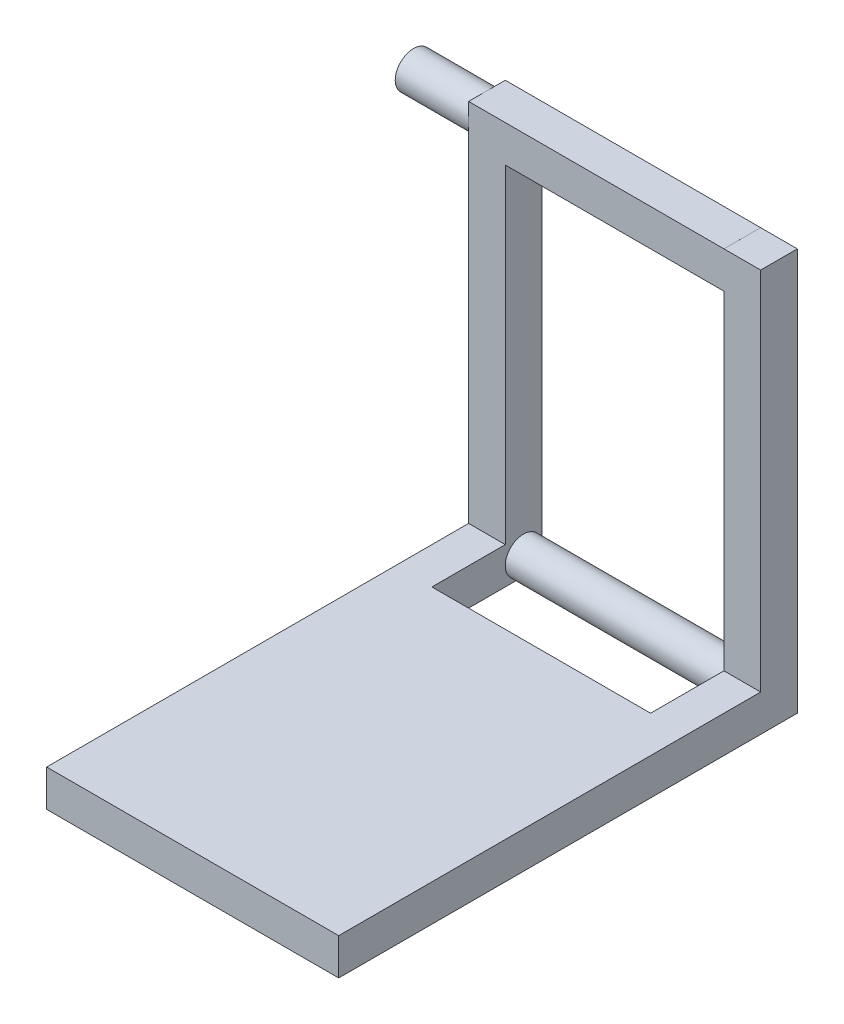
SolidWorks part; units mm, degrees
ref_plane "Front Plane" through (0, 0, 0) normal (0, 0, 1) x (1, 0, 0)
ref_plane "Top Plane" through (0, 0, 0) normal (0, 1, 0) x (1, 0, 0)
ref_plane "Right Plane" through (0, 0, 0) normal (1, 0, 0) x (0, 0, -1)
sketch "Sketch2" plane through (0, 0, 0) normal (0, 1, 0) x (1, 0, 0)
  line L1 (-0.4885, 0.9749) -> (1.5115, 0.9749)
  line L2 (-0.4885, 0.9749) -> (-0.4885, -1.0251)
  line L3 (-0.4885, -1.0251) -> (1.5115, -1.0251)
  line L4 (1.5115, 0.9749) -> (1.5115, -1.0251)
  dimension "D1" = 2
extrude "Boss-Extrude2" add sketch "Sketch2" along normal blind 21.92
ref_plane "Plane1" through (1.5115, 0, 0) normal (1, 0, 0) x (0, 0, -1)
sketch "Sketch3" plane through (1.5115, 0, 0) normal (1, 0, 0) x (0, 0, -1)
  circle A0 centre (-0.0297, 0.9996) radius 1
  dimension "D1" = 2
extrude "Boss-Extrude3" add sketch "Sketch3" along normal blind 11.92 contours A0
ref_plane "Plane3" through (-0.4885, 0, 0) normal (-1, 0, 0) x (0, 0, 1)
sketch "Sketch5" plane through (-0.4885, 0, 0) normal (-1, 0, 0) x (0, 0, 1)
  line L0 (1.0251, 21.92) -> (1.0251, 0) construction
  line L1 (-0.9749, 21.92) -> (1.0251, 21.92) construction
  circle A0 centre (0.0251, 20.92) radius 1
  dimension "D1" = 2
extrude "Boss-Extrude5" add sketch "Sketch5" along normal blind 4
ref_plane "Plane4" through (13.4315, 0, 0) normal (1, 0, 0) x (0, 0, -1)
sketch "Sketch6" plane through (13.4315, 0, 0) normal (1, 0, 0) x (0, 0, -1)
  line L1 (-0.7368, 1.7067) -> (0.6774, 1.7067)
  line L2 (-0.7368, 1.7067) -> (-0.7368, 0.2925)
  line L3 (-0.7368, 0.2925) -> (0.6774, 0.2925)
  line L4 (0.6774, 1.7067) -> (0.6774, 0.2925)
  circle A0 centre (-0.0297, 0.9996) radius 1 construction
  arc A1 (0, 0) -> (-1.0251, 1.0958) centre (-0.0297, 0.9996) ccw construction
  point P4 (0, 0)
  point P7 (0, 0)
  point P8 (0, 0)
  point P9 (0, 0)
sketch "Sketch12" plane through (13.4315, 0, 0) normal (1, 0, 0) x (0, 0, -1)
  line L0 (-1.0251, 0.9033) -> (-1.0251, 0) construction
  line L1 (-1.0251, 1.9996) -> (0.9749, 1.9996)
  line L2 (-1.0251, 1.9996) -> (-1.0251, 0)
  line L3 (-1.0251, 0) -> (0.9749, 0)
  line L4 (0.9749, 1.9996) -> (0.9749, 0)
  line L5 (-1.0251, 0) -> (-0.0594, 0) construction
  circle A0 centre (-0.0297, 0.9996) radius 1 construction
  point P5 (-1.0251, 0)
extrude "Boss-Extrude9" add sketch "Sketch12" along normal blind 2
ref_plane "Plane7" through (0, 1.9996, 0) normal (0, 1, 0) x (1, 0, 0)
sketch "Sketch13" plane through (0, 1.9996, 0) normal (0, 1, 0) x (1, 0, 0)
  line L0 (13.4315, -0.7778) -> (13.4315, 0.7778) construction
  line L1 (15.4315, 0.9749) -> (13.4315, 0.9749)
  line L2 (15.4315, 0.9749) -> (15.4315, -1.0251)
  line L3 (15.4315, -1.0251) -> (13.4315, -1.0251)
  line L4 (13.4315, 0.9749) -> (13.4315, -1.0251)
sketch "Sketch14" plane through (1.5115, 0, 0) normal (1, 0, 0) x (0, 0, -1)
  line L0 (0.9749, 21.92) -> (0.9749, 0) construction
  line L1 (-1.0251, 21.92) -> (0.9749, 21.92)
  line L2 (-1.0251, 21.92) -> (-1.0251, 19.92)
  line L3 (-1.0251, 19.92) -> (0.9749, 19.92)
  line L4 (0.9749, 21.92) -> (0.9749, 19.92)
extrude "Boss-Extrude10" add sketch "Sketch14" along normal blind 11.92
extrude "Boss-Extrude11" add sketch "Sketch13" along normal blind 19.92
ref_plane "Plane8" through (0, 0, 1.0251) normal (0, 0, 1) x (1, 0, 0)
sketch "Sketch16" plane through (0, 0, 1.0251) normal (0, 0, 1) x (1, 0, 0)
  line L0 (55, 1.9996) -> (-55, 1.9996) construction
  line L1 (15.4315, 0) -> (13.4315, 0)
  line L2 (15.4315, 0) -> (15.4315, 1.9996)
  line L3 (15.4315, 1.9996) -> (13.4315, 1.9996)
  line L4 (13.4315, 0) -> (13.4315, 1.9996)
  line L5 (13.4315, 1.9996) -> (13.4315, 0) construction
extrude "Boss-Extrude13" add sketch "Sketch16" along normal blind 4
sketch "Sketch17" plane through (0, 0, 1.0251) normal (0, 0, 1) x (1, 0, 0)
  line L0 (55, 1.9996) -> (-55, 1.9996) construction
  line L1 (-0.4885, 0) -> (1.5115, 0)
  line L2 (-0.4885, 0) -> (-0.4885, 1.9996)
  line L3 (-0.4885, 1.9996) -> (1.5115, 1.9996)
  line L4 (1.5115, 0) -> (1.5115, 1.9996)
  line L5 (1.5115, 19.92) -> (1.5115, 1.0958) construction
extrude "Boss-Extrude14" add sketch "Sketch17" along normal blind 4
sketch "Sketch18" plane through (0, 0, 5.0251) normal (0, 0, 1) x (1, 0, 0)
  line L0 (55, 1.9996) -> (-55, 1.9996) construction
  line L1 (-0.4885, 0) -> (15.4315, 0)
  line L2 (-0.4885, 0) -> (-0.4885, 1.9996)
  line L3 (-0.4885, 1.9996) -> (15.4315, 1.9996)
  line L4 (15.4315, 0) -> (15.4315, 1.9996)
  line L5 (15.4315, 0) -> (15.4315, 1.9996) construction
extrude "Boss-Extrude16" add sketch "Sketch18" along normal blind 19
